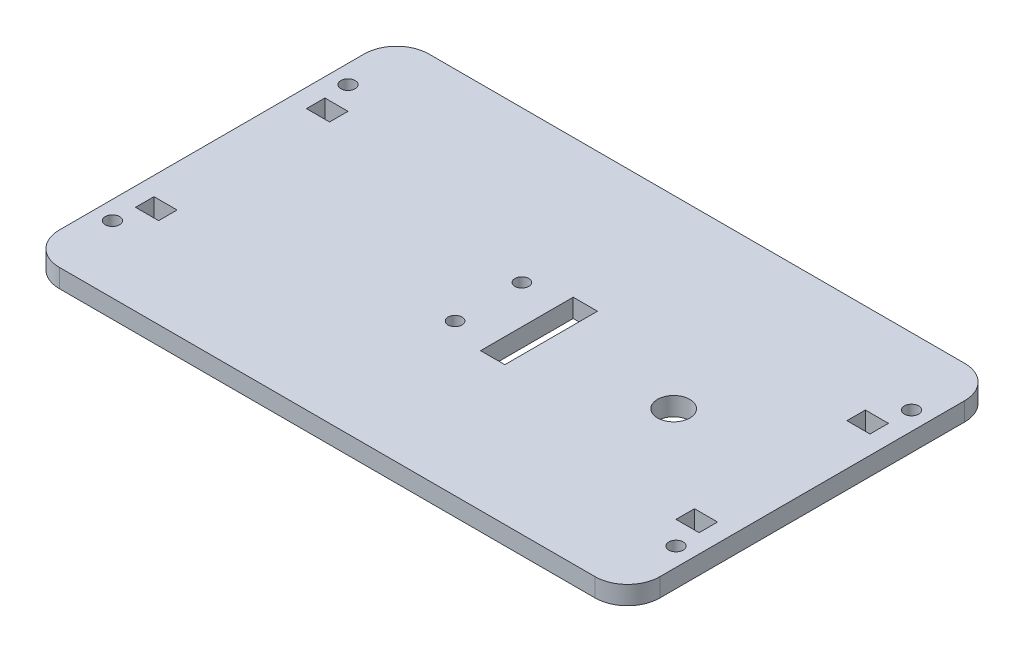
SolidWorks part; units mm, degrees
ref_plane "Front Plane" through (0, 0, 0) normal (0, 0, 1) x (1, 0, 0)
ref_plane "Top Plane" through (0, 0, 0) normal (0, 1, 0) x (1, 0, 0)
ref_plane "Right Plane" through (0, 0, 0) normal (1, 0, 0) x (0, 0, -1)
sketch "Sketch1" plane through (0, 0, 0) normal (0, 1, 0) x (1, 0, 0)
  line L0 (0, 0) -> (0, 18.9717) construction
  line L1 (-58, -40) -> (58, -40)
  line L2 (-65, -33) -> (-65, 33)
  line L3 (-58, 40) -> (58, 40)
  line L4 (65, -33) -> (65, 33)
  line L5 (-65, -40) -> (65, 40) construction
  line L6 (-65, 40) -> (65, -40) construction
  line L7 (61, 20.5) -> (56, 20.5)
  line L8 (61, 20.5) -> (61, 16.5)
  line L9 (61, 16.5) -> (56, 16.5)
  line L10 (56, 20.5) -> (56, 16.5)
  line L11 (0, 0) -> (21.4077, 0) construction
  line L12 (61, -16.5) -> (56, -16.5)
  line L13 (56, -20.5) -> (56, -16.5)
  line L14 (61, -20.5) -> (56, -20.5)
  line L15 (61, -20.5) -> (61, -16.5)
  line L16 (-61, -20.5) -> (-61, -16.5)
  line L17 (-61, -20.5) -> (-56, -20.5)
  line L18 (-56, -20.5) -> (-56, -16.5)
  line L19 (-61, -16.5) -> (-56, -16.5)
  line L20 (-61, 16.5) -> (-56, 16.5)
  line L21 (-56, 20.5) -> (-56, 16.5)
  line L22 (-61, 20.5) -> (-56, 20.5)
  line L23 (-61, 20.5) -> (-61, 16.5)
  line L24 (-7.85, 10.0275) -> (7.85, 10.0275) construction
  line L25 (3.2223, 10.0275) -> (8.4756, 10.0275)
  line L26 (3.2223, 10.0275) -> (3.2223, -10.0275)
  line L27 (3.2223, -10.0275) -> (8.4756, -10.0275)
  line L28 (8.4756, 10.0275) -> (8.4756, -10.0275)
  circle A0 centre (61, 25.5) radius 1.55
  circle A1 centre (61, -25.5) radius 1.55
  circle A2 centre (-61, -25.5) radius 1.55
  circle A3 centre (-61, 25.5) radius 1.55
  circle A4 centre (-5.1, -7.2275) radius 1.5
  circle A5 centre (-5.1, -7.2275) radius 1.5 construction
  circle A6 centre (-5.1, 7.2275) radius 1.5
  circle A7 centre (-5.1, 7.2275) radius 1.5 construction
  circle A8 centre (35, 0) radius 3.5
  arc A9 (58, 40) -> (65, 33) centre (58, 33) cw
  arc A10 (58, -40) -> (65, -33) centre (58, -33) ccw
  arc A11 (-58, -40) -> (-65, -33) centre (-58, -33) cw
  arc A12 (-65, 33) -> (-58, 40) centre (-58, 33) cw
  point P0 (0, 0)
  point P48 (3.2223, 0)
  dimension "D8" = 3.1
  dimension "D12" = 7
  dimension "D13" = 7
  dimension "D1" = 80
  dimension "D2" = 130
  dimension "D3" = 4
  dimension "D4" = 19.5
  dimension "D5" = 4
  dimension "D6" = 5
  dimension "D7" = 14.5
  dimension "D9" = 3.2223
  dimension "D10" = 5.2533
  dimension "D11" = 35
extrude "Boss-Extrude1" add sketch "Sketch1" along normal blind 4
